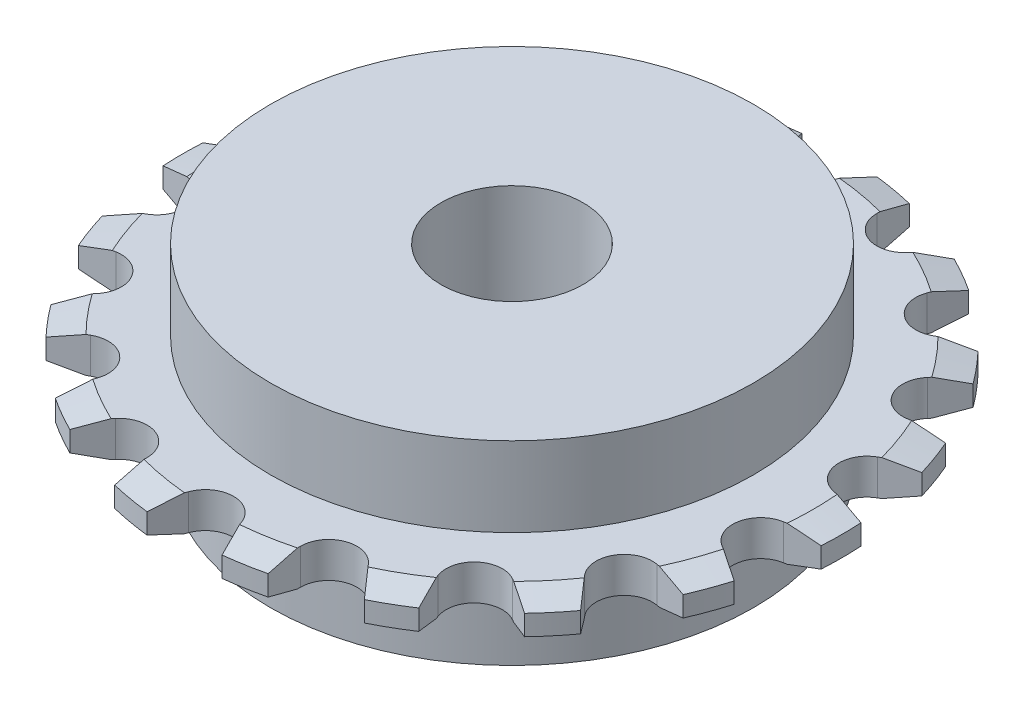
SolidWorks part; units mm, degrees
material "Plain Carbon Steel"
ref_plane "Front Plane" through (0, 0, 0) normal (0, 0, 1) x (1, 0, 0)
ref_plane "Top Plane" through (0, 0, 0) normal (0, 1, 0) x (1, 0, 0)
ref_plane "Right Plane" through (0, 0, 0) normal (1, 0, 0) x (0, 0, -1)
sketch "Sketch1" plane through (0, 0, 0) normal (0, 1, 0) x (1, 0, 0)
  circle A0 centre (0, 0) radius 29.4686
  circle A1 centre (0, 0) radius 6.35
  dimension "D1" = 58.9372
  dimension "D2" = 12.7
extrude "Boss-Extrude1" add sketch "Sketch1" along normal blind 3.175
chamfer "Chamfer1" distance 2.54 angle 15 2 edges at (0, 0, 29.4686) (0, 3.175, 29.4686)
sketch "Sketch3" plane through (0, 3.175, 0) normal (0, 1, 0) x (1, 0, 0)
  line L0 (0, 29.4686) -> (0, -29.4686) construction
  line L1 (2.363, 26.5512) -> (3.3551, 29.277)
  line L2 (-2.363, 26.5512) -> (-3.3551, 29.277)
  line L3 (6.8606, 25.7581) -> (6.8606, 28.6589)
  line L4 (11.3015, 24.1418) -> (13.1661, 26.3639)
  line L5 (15.2566, 21.8583) -> (16.2488, 24.5841)
  line L6 (18.8769, 18.8205) -> (21.389, 20.2709)
  line L7 (21.8125, 15.322) -> (23.6771, 17.5441)
  line L8 (24.1755, 11.2292) -> (27.0322, 11.7329)
  line L9 (25.7375, 6.9376) -> (28.2496, 8.388)
  line L10 (26.5581, 2.2835) -> (29.4148, 1.7798)
  line L11 (26.5581, -2.2835) -> (29.4148, -1.7798)
  line L12 (25.7375, -6.9376) -> (28.2496, -8.388)
  line L13 (24.1755, -11.2292) -> (27.0322, -11.7329)
  line L14 (21.8125, -15.322) -> (23.6771, -17.5441)
  line L15 (18.8769, -18.8205) -> (21.389, -20.2709)
  line L16 (15.2566, -21.8583) -> (16.2488, -24.5841)
  line L17 (11.3015, -24.1418) -> (13.1661, -26.3639)
  line L18 (6.8606, -25.7581) -> (6.8606, -28.6589)
  line L19 (2.363, -26.5512) -> (3.3551, -29.277)
  line L20 (-2.363, -26.5512) -> (-3.3551, -29.277)
  line L21 (-6.8606, -25.7581) -> (-6.8606, -28.6589)
  line L22 (-11.3015, -24.1418) -> (-13.1661, -26.3639)
  line L23 (-15.2566, -21.8583) -> (-16.2488, -24.5841)
  line L24 (-18.8769, -18.8205) -> (-21.389, -20.2709)
  line L25 (-21.8125, -15.322) -> (-23.6771, -17.5441)
  line L26 (-24.1755, -11.2292) -> (-27.0322, -11.7329)
  line L27 (-25.7375, -6.9376) -> (-28.2496, -8.388)
  line L28 (-26.5581, -2.2835) -> (-29.4148, -1.7798)
  line L29 (-26.5581, 2.2835) -> (-29.4148, 1.7798)
  line L30 (-25.7375, 6.9376) -> (-28.2496, 8.388)
  line L31 (-24.1755, 11.2292) -> (-27.0322, 11.7329)
  line L32 (-21.8125, 15.322) -> (-23.6771, 17.5441)
  line L33 (-18.8769, 18.8205) -> (-21.389, 20.2709)
  line L34 (-15.2566, 21.8583) -> (-16.2488, 24.5841)
  line L35 (-11.3015, 24.1418) -> (-13.1661, 26.3639)
  line L36 (-6.8606, 25.7581) -> (-6.8606, 28.6589)
  circle A0 centre (0, 0) radius 27.4112 construction
  circle A1 centre (0, 0) radius 29.4686 construction
  arc A2 (-2.363, 26.5512) -> (2.363, 26.5512) centre (0, 27.4112) ccw
  arc A3 (3.3551, 29.277) -> (-3.3551, 29.277) centre (0, 0) ccw
  arc A4 (6.8606, 25.7581) -> (11.3015, 24.1418) centre (9.3752, 25.7581) ccw
  arc A5 (13.1661, 26.3639) -> (6.8606, 28.6589) centre (0, 0) ccw
  arc A6 (15.2566, 21.8583) -> (18.8769, 18.8205) centre (17.6196, 20.9982) ccw
  arc A7 (21.389, 20.2709) -> (16.2488, 24.5841) centre (0, 0) ccw
  arc A8 (21.8125, 15.322) -> (24.1755, 11.2292) centre (23.7388, 13.7056) ccw
  arc A9 (27.0322, 11.7329) -> (23.6771, 17.5441) centre (0, 0) ccw
  arc A10 (25.7375, 6.9376) -> (26.5581, 2.2835) centre (26.9948, 4.7599) ccw
  arc A11 (29.4148, 1.7798) -> (28.2496, 8.388) centre (0, 0) ccw
  arc A12 (26.5581, -2.2835) -> (25.7375, -6.9376) centre (26.9948, -4.7599) ccw
  arc A13 (28.2496, -8.388) -> (29.4148, -1.7798) centre (0, 0) ccw
  arc A14 (24.1755, -11.2292) -> (21.8125, -15.322) centre (23.7388, -13.7056) ccw
  arc A15 (23.6771, -17.5441) -> (27.0322, -11.7329) centre (0, 0) ccw
  arc A16 (18.8769, -18.8205) -> (15.2566, -21.8583) centre (17.6196, -20.9982) ccw
  arc A17 (16.2488, -24.5841) -> (21.389, -20.2709) centre (0, 0) ccw
  arc A18 (11.3015, -24.1418) -> (6.8606, -25.7581) centre (9.3752, -25.7581) ccw
  arc A19 (6.8606, -28.6589) -> (13.1661, -26.3639) centre (0, 0) ccw
  arc A20 (2.363, -26.5512) -> (-2.363, -26.5512) centre (0, -27.4112) ccw
  arc A21 (-3.3551, -29.277) -> (3.3551, -29.277) centre (0, 0) ccw
  arc A22 (-6.8606, -25.7581) -> (-11.3015, -24.1418) centre (-9.3752, -25.7581) ccw
  arc A23 (-13.1661, -26.3639) -> (-6.8606, -28.6589) centre (0, 0) ccw
  arc A24 (-15.2566, -21.8583) -> (-18.8769, -18.8205) centre (-17.6196, -20.9982) ccw
  arc A25 (-21.389, -20.2709) -> (-16.2488, -24.5841) centre (0, 0) ccw
  arc A26 (-21.8125, -15.322) -> (-24.1755, -11.2292) centre (-23.7388, -13.7056) ccw
  arc A27 (-27.0322, -11.7329) -> (-23.6771, -17.5441) centre (0, 0) ccw
  arc A28 (-25.7375, -6.9376) -> (-26.5581, -2.2835) centre (-26.9948, -4.7599) ccw
  arc A29 (-29.4148, -1.7798) -> (-28.2496, -8.388) centre (0, 0) ccw
  arc A30 (-26.5581, 2.2835) -> (-25.7375, 6.9376) centre (-26.9948, 4.7599) ccw
  arc A31 (-28.2496, 8.388) -> (-29.4148, 1.7798) centre (0, 0) ccw
  arc A32 (-24.1755, 11.2292) -> (-21.8125, 15.322) centre (-23.7388, 13.7056) ccw
  arc A33 (-23.6771, 17.5441) -> (-27.0322, 11.7329) centre (0, 0) ccw
  arc A34 (-18.8769, 18.8205) -> (-15.2566, 21.8583) centre (-17.6196, 20.9982) ccw
  arc A35 (-16.2488, 24.5841) -> (-21.389, 20.2709) centre (0, 0) ccw
  arc A36 (-11.3015, 24.1418) -> (-6.8606, 25.7581) centre (-9.3752, 25.7581) ccw
  arc A37 (-6.8606, 28.6589) -> (-13.1661, 26.3639) centre (0, 0) ccw
  point P121 (0, 0)
  dimension "D1" = 54.8224
  dimension "D3" = 2.5146
  dimension "D2" = 20
  dimension "D4" = 18
extrude "Cut-Extrude2" cut sketch "Sketch3" against normal through all
sketch "Sketch4" plane through (0, 3.175, 0) normal (0, 1, 0) x (1, 0, 0)
  circle A0 centre (0, 0) radius 6.35
  circle A1 centre (0, 0) radius 21.59
  dimension "D1" = 43.18
  dimension "D2" = 12.7
extrude "Boss-Extrude2" add sketch "Sketch4" along normal blind 7.112 and the other way blind 10.287
